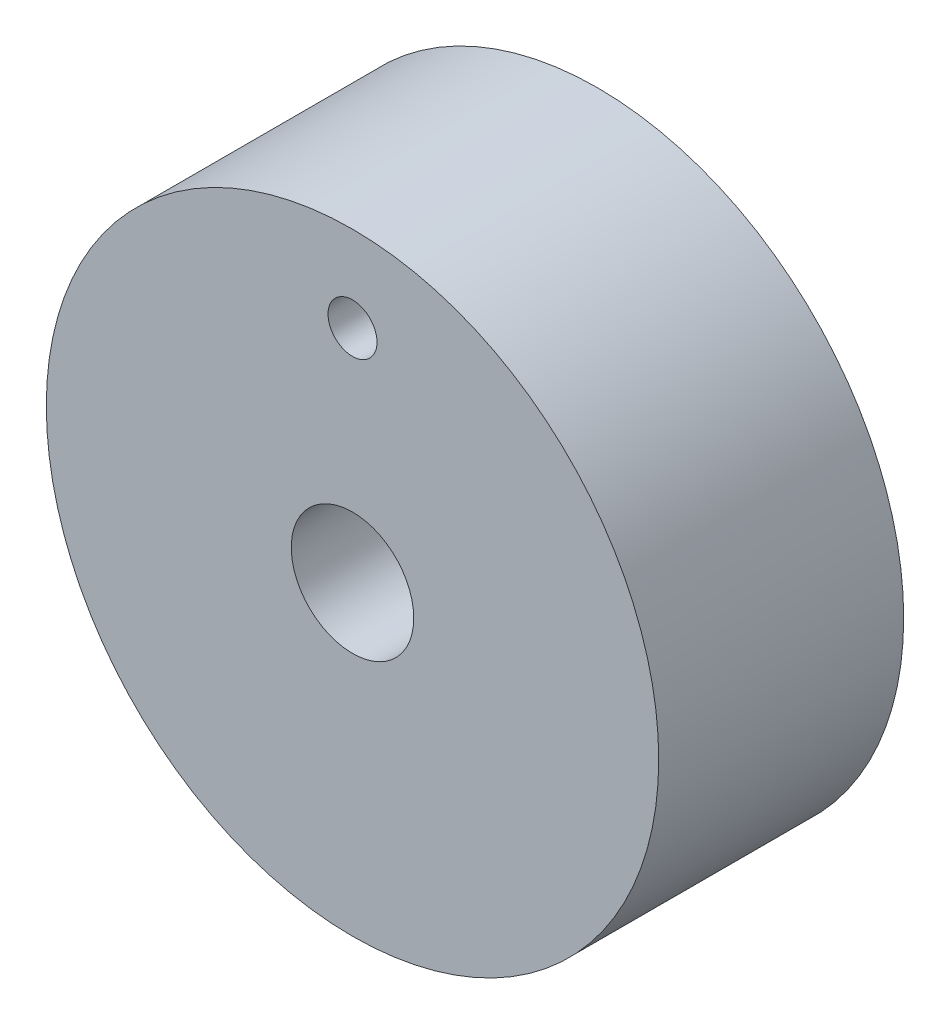
SolidWorks part; units mm, degrees
ref_plane "Front Plane" through (0, 0, 0) normal (0, 0, 1) x (1, 0, 0)
ref_plane "Top Plane" through (0, 0, 0) normal (0, 1, 0) x (1, 0, 0)
ref_plane "Right Plane" through (0, 0, 0) normal (1, 0, 0) x (0, 0, -1)
sketch "Sketch1" plane through (0, 0, 0) normal (0, 0, 1) x (1, 0, 0)
  line L0 (0, -55) -> (0, 55) construction
  circle A0 centre (0, 0) radius 25
  circle A1 centre (0, 0) radius 5
  circle A2 centre (0, 18) radius 2
  point P8 (0, 0)
  dimension "D1" = 50
  dimension "D2" = 10
  dimension "D4" = 4
  dimension "D3" = 18
extrude "Boss-Extrude1" add sketch "Sketch1" along normal mid plane 20
